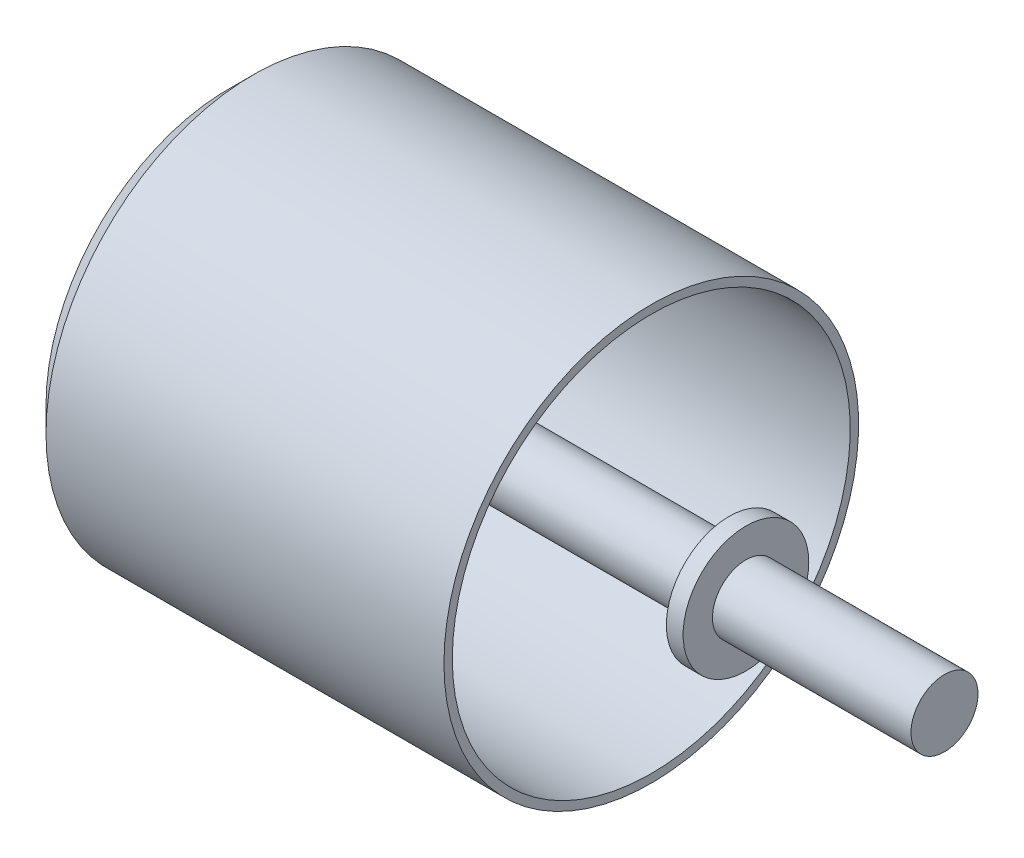
SolidWorks part; units mm, degrees
ref_plane "Front Plane" through (0, 0, 0) normal (0, 0, 1) x (1, 0, 0)
ref_plane "Top Plane" through (0, 0, 0) normal (0, 1, 0) x (1, 0, 0)
ref_plane "Right Plane" through (0, 0, 0) normal (1, 0, 0) x (0, 0, -1)
sketch "Sketch1" plane through (0, 0, 0) normal (0, 0, 1) x (1, 0, 0)
  line L0 (0, 0) -> (80.0956, 0) construction
  line L1 (0, 21.75) -> (3, 24.75)
  line L3 (0, 0) -> (0, 21.75)
  line L4 (0, 0) -> (1, 0)
  line L6 (1, 0) -> (1, 21.3358)
  line L7 (1, 21.3358) -> (3.4142, 23.75)
  line L8 (3.4142, 23.75) -> (50.5, 23.75)
  line L9 (50.5, 23.75) -> (50.5, 24.75)
  line L15 (3, 24.75) -> (50.5, 24.75)
  dimension "D1" = 135
  dimension "D2" = 1
  dimension "D3" = 1
  dimension "D4" = 49.5
  dimension "D5" = 50.5
  dimension "D6" = 47.5
revolve "Revolve1" add sketch "Sketch1" angle 360 about L0
sketch "Sketch2" plane through (0, 0, 0) normal (1, 0, 0) x (0, 0, -1)
  circle A0 centre (0, 0) radius 4
  dimension "D1" = 8
extrude "Boss-Extrude1" add sketch "Sketch2" along normal blind 85.5
sketch "Sketch3" plane through (0, 0, 0) normal (-1, 0, 0) x (0, 0, 1)
  line L0 (-17, 0) -> (17, 0) construction
  line L1 (0, 17) -> (0, -17) construction
  circle A0 centre (0, 17) radius 3.5
  circle A1 centre (17, 0) radius 3.5
  circle A2 centre (0, -17) radius 3.5
  circle A3 centre (-17, 0) radius 3.5
  circle A4 centre (0, 0) radius 17 construction
  dimension "D1" = 34
  dimension "D2" = 7
extrude "Cut-Extrude1" cut sketch "Sketch3" against normal through all
sketch "Sketch4" plane through (59.8, 0, 0) normal (1, 0, 0) x (0, 0, -1)
  circle A0 centre (0, 0) radius 7.5
  dimension "D1" = 15
extrude "Boss-Extrude2" add sketch "Sketch4" along normal blind 2
